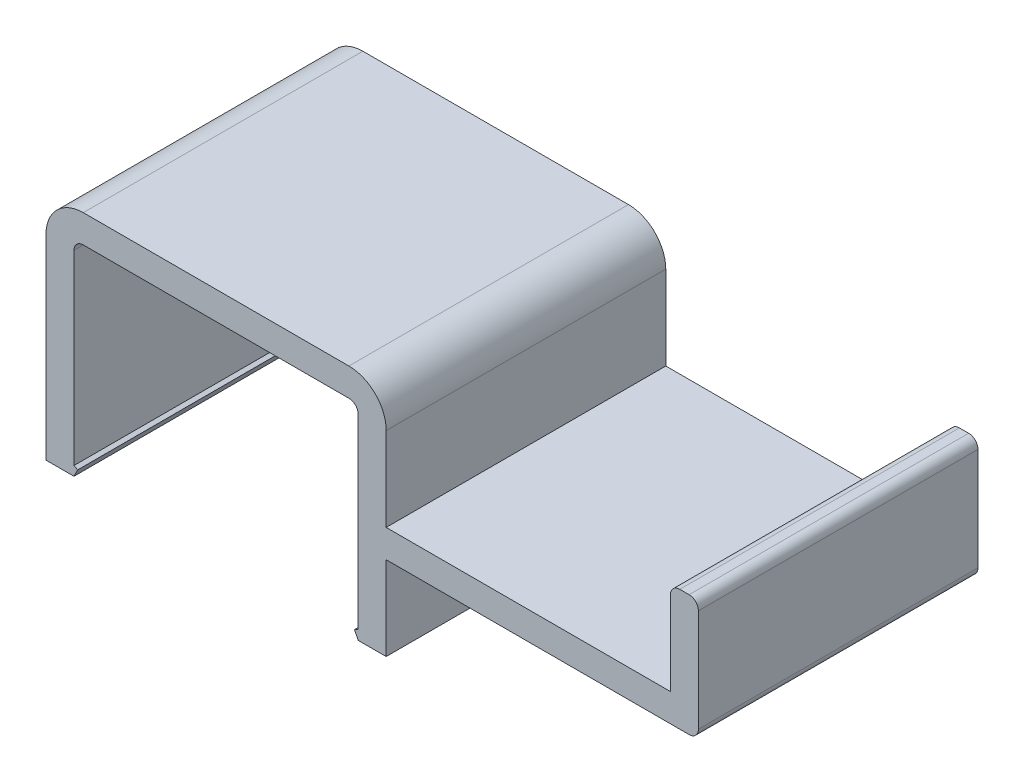
SolidWorks part; units mm, degrees
ref_plane "Front Plane" through (0, 0, 0) normal (0, 0, 1) x (1, 0, 0)
ref_plane "Top Plane" through (0, 0, 0) normal (0, 1, 0) x (1, 0, 0)
ref_plane "Right Plane" through (0, 0, 0) normal (1, 0, 0) x (0, 0, -1)
sketch "Sketch1" plane through (0, 0, 0) normal (0, 0, 1) x (1, 0, 0)
  line L1 (-14, 8.5) -> (14.5, 8.5)
  line L2 (-15, 7.5) -> (-15, -12.5)
  line L4 (15.5, 7.5) -> (15.5, -12.5)
  arc A0 (14.5, 8.5) -> (15.5, 7.5) centre (14.5, 7.5) cw
  arc A1 (-14, 8.5) -> (-15, 7.5) centre (-14, 7.5) ccw
  point P0 (0, 0)
  point P11 (14.5, 8.285)
  dimension "D1" = 1
extrude "Extrude-Thin1" add sketch "Sketch1" along normal blind 30 thin thin type one direction wall 3
sketch "Sketch2" plane through (0, 0, 30) normal (0, 0, 1) x (1, 0, 0)
  line L3 (-15, -13.5) -> (-18, -13.5)
  line L4 (-18, -13.5) -> (-18, -12.5)
  line L8 (0.25, 8.5) -> (0.25, -16.4103) construction
  line L14 (-18, -12.5) -> (-15, -12.5)
  line L17 (-15, -13.5) -> (-14.6, -12.7)
  line L18 (-15, -12.5) -> (-14.6, -12.7)
  line L24 (14.5, 8.5) -> (-14, 8.5) construction
  line L25 (15.5, -12.5) -> (15.1, -12.7)
  line L26 (15.5, -13.5) -> (15.1, -12.7)
  line L27 (18.5, -12.5) -> (15.5, -12.5)
  line L28 (18.5, -13.5) -> (18.5, -12.5)
  line L29 (15.5, -13.5) -> (18.5, -13.5)
extrude "Boss-Extrude1" add sketch "Sketch2" against normal blind 30
sketch "Sketch3" plane through (18.5, 0, 0) normal (1, 0, 0) x (0, 0, -1)
  line L0 (-30, -3) -> (0, -3)
  line L1 (-30, -13.5) -> (-30, 7.5) construction
  line L2 (0, -13.5) -> (0, 7.5) construction
extrude "Extrude-Thin2" add sketch "Sketch3" along normal blind 30 thin thin type mid plane wall 3
sketch "Sketch4" plane through (0, 0, 30) normal (0, 0, 1) x (1, 0, 0)
  line L0 (48.5, -1.5) -> (49, -1.5)
  line L1 (49, -1.5) -> (49, 7.5)
  line L2 (50, 8.5) -> (51, 8.5)
  line L3 (48.5, -4.5) -> (51, -4.5)
  line L4 (52, -3.5) -> (52, 7.5)
  line L5 (48.5, -1.5) -> (48.5, -4.5)
  arc A0 (51, -4.5) -> (52, -3.5) centre (51, -3.5) ccw
  arc A1 (51, 8.5) -> (52, 7.5) centre (51, 7.5) cw
  arc A2 (49, 7.5) -> (50, 8.5) centre (50, 7.5) cw
  dimension "D1" = 1
extrude "Boss-Extrude2" add sketch "Sketch4" against normal blind 30
